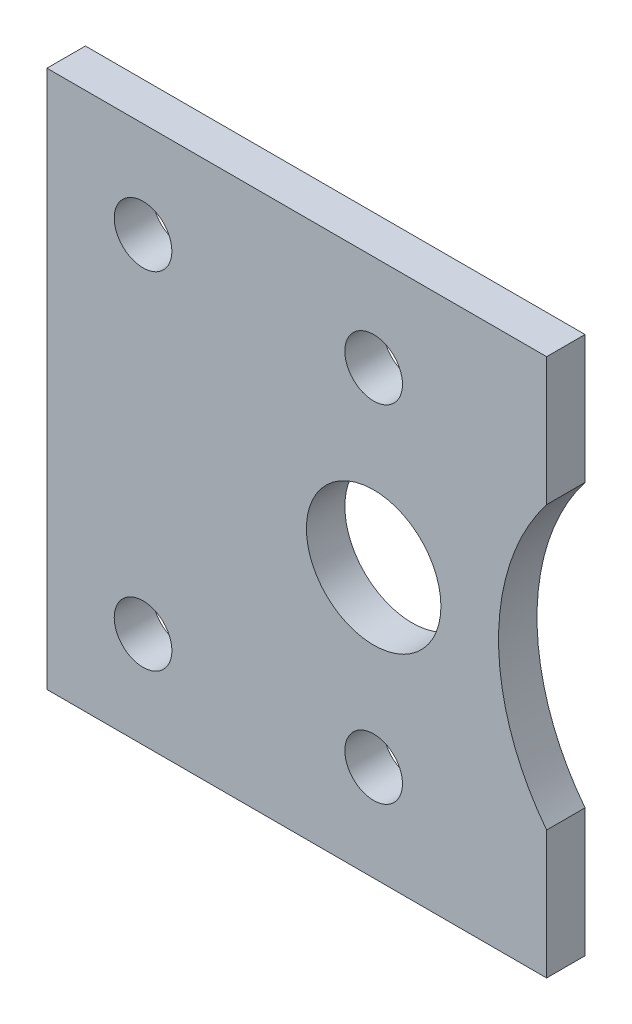
SolidWorks part; units mm, degrees
ref_plane "Front Plane" through (0, 0, 0) normal (0, 0, 1) x (1, 0, 0)
ref_plane "Top Plane" through (0, 0, 0) normal (0, 1, 0) x (1, 0, 0)
ref_plane "Right Plane" through (0, 0, 0) normal (1, 0, 0) x (0, 0, -1)
sketch "Sketch1" plane through (0, 0, 0) normal (0, 0, 1) x (1, 0, 0)
  line L0 (9, -14) -> (9, -7.3314)
  line L1 (0, -15.4) -> (0, 15.4) construction
  line L2 (9, 14) -> (-17, 14)
  line L3 (-17, 14) -> (-17, -14)
  line L4 (-17, -14) -> (9, -14)
  line L5 (55, 0) -> (-55, 0) construction
  line L6 (9, 7.3314) -> (9, 14)
  circle A0 centre (0, 0) radius 3.5
  arc A1 (9, 7.3314) -> (9, -7.3314) centre (18.5, 0) ccw
  circle A2 centre (-12, 9) radius 1.5
  circle A3 centre (0, 9) radius 1.5
  circle A4 centre (-12, -9) radius 1.5
  circle A5 centre (0, -9) radius 1.5
  point P8 (3.5, 0)
  point P13 (6.5, 0)
  point P16 (0, 0)
  point P17 (-17, 0)
  dimension "D3" = 24
  dimension "D4" = 7
  dimension "D8" = 3
  dimension "D1" = 26
  dimension "D2" = 28
  dimension "D5" = 3
  dimension "D6" = 5
  dimension "D7" = 5
  dimension "D9" = 17
  dimension "D10" = 2
extrude "Boss-Extrude1" add sketch "Sketch1" along normal blind 2
